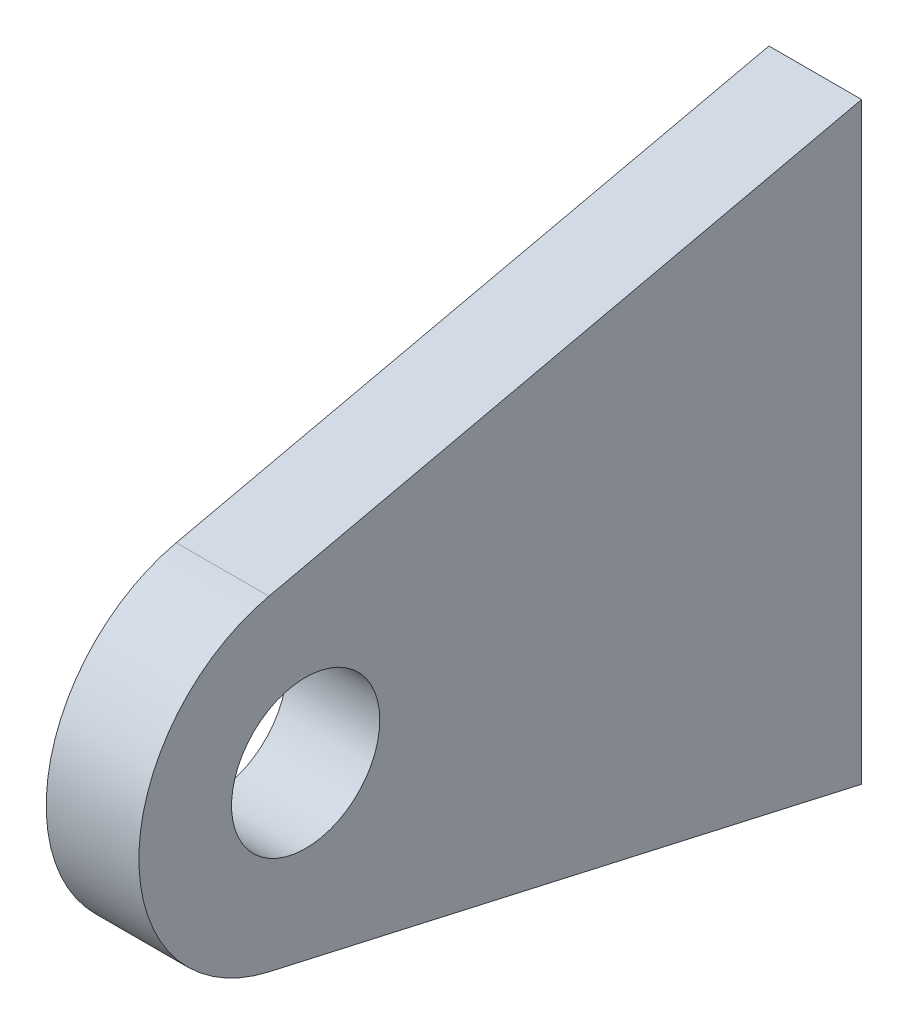
SolidWorks part; units mm, degrees
ref_plane "Front Plane" through (0, 0, 0) normal (1, 0, 0) x (0, 1, 0)
ref_plane "Top Plane" through (0, 0, 0) normal (0, 0, 1) x (0, 1, 0)
ref_plane "Right Plane" through (0, 0, 0) normal (0, 1, 0) x (-1, 0, 0)
sketch "Sketch1" plane through (0, 0, 0) normal (1, 0, 0) x (0, 1, 0)
  line L0 (-16, 0) -> (16, 0)
  line L1 (0, 0) -> (0, 30) construction
  line L2 (-16, 0) -> (-8.779, 31.9821)
  line L3 (16, 0) -> (8.779, 31.9821)
  circle A0 centre (0, 30) radius 4
  arc A1 (8.779, 31.9821) -> (-8.779, 31.9821) centre (0, 30) ccw
  arc A2 (-8.779, 31.9821) -> (0, 21) centre (0, 30) ccw construction
  arc A3 (0, 21) -> (8.779, 31.9821) centre (0, 30) ccw construction
  point P4 (0, 0)
  dimension "D2" = 8
  dimension "D3" = 5
  dimension "D1" = 32
  dimension "D4" = 30
extrude "Boss-Extrude1" add sketch "Sketch1" along normal mid plane 5
ref_point "Point1"
sketch "Sketch3" plane through (0, 0, 0) normal (0, 1, 0) x (-1, 0, 0)
  line L0 (-2.5, 0) -> (2.5, 0) construction
  line L1 (-2.5, 0) -> (2.5, 0)
  line L2 (0, 30) -> (0, 0) construction
  line L3 (0, 0) -> (0, -15.875) construction
  dimension "D1" = 15.875
